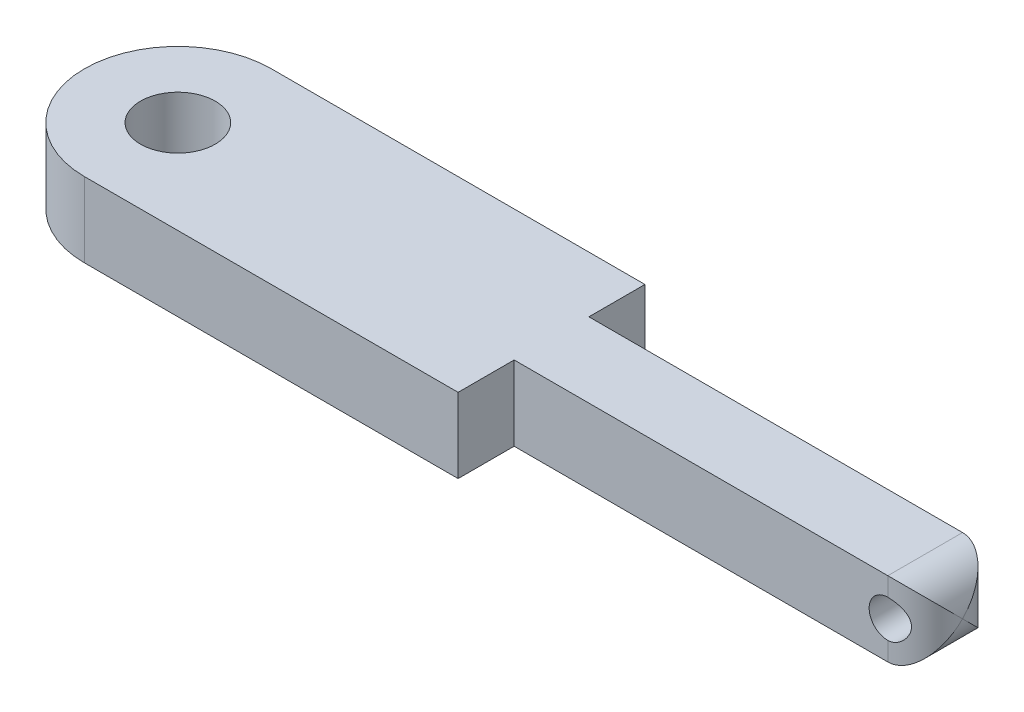
SolidWorks part; units mm, degrees
ref_plane "Front Plane" through (0, 0, 0) normal (0, 0, 1) x (1, 0, 0)
ref_plane "Top Plane" through (0, 0, 0) normal (0, 1, 0) x (1, 0, 0)
ref_plane "Right Plane" through (0, 0, 0) normal (1, 0, 0) x (0, 0, -1)
sketch "Sketch1" plane through (0, 0, 0) normal (0, 1, 0) x (1, 0, 0)
  line L0 (-10, 0) -> (0, 0) construction
  line L1 (-10, 2.5) -> (0, 2.5)
  line L2 (-10, -2.5) -> (0, -2.5)
  line L3 (0, 2.5) -> (0, -2.5)
  arc A0 (-10, 2.5) -> (-10, -2.5) centre (-10, 0) ccw
  circle A3 centre (-10, 0) radius 1
  point P3 (0, 0)
  dimension "D3" = 2
  dimension "D4" = 2.5
  dimension "D5" = 10
  dimension "D6" = 2.5
  dimension "D2" = 5
  dimension "D12" = 10
extrude "Boss-Extrude1" add sketch "Sketch1" along normal blind 2
sketch "Sketch2" plane through (0, 0, 0) normal (0, 0, 1) x (1, 0, 0)
  line L1 (0.0125, 0) -> (-0.0002, 0)
  line L5 (-10, 0) -> (0, 0) construction
  point P2 (0.0125, 1)
  dimension "D2" = 0
sketch "Sketch4" plane through (0, 0, 0) normal (1, 0, 0) x (0, 0, -1)
  line L1 (-1, 2) -> (1, 2)
  line L2 (-1, 2) -> (-1, 0)
  line L3 (-1, 0) -> (1, 0)
  line L4 (1, 2) -> (1, 0)
  line L5 (-1, 2) -> (1, 0) construction
  line L6 (-1, 0) -> (1, 2) construction
  point P0 (0, 1)
  dimension "D1" = 2
  dimension "D2" = 2
extrude "Boss-Extrude2" add sketch "Sketch4" along normal blind 11
ref_plane "Plane1" through (0, 0, 0) normal (0, 0, 1) x (1, 0, 0)
sketch "Sketch5" plane through (0, 2, 0) normal (0, 1, 0) x (1, 0, 0)
  line L2 (11, 1) -> (0, 1) construction
  line L3 (11, -1) -> (0, -1) construction
  line L4 (10, 1) -> (10, 1.5)
  line L5 (10, 1.5) -> (12, 1.5)
  line L6 (12, 1.5) -> (12, -1.5)
  line L7 (12, -1.5) -> (10, -1.5)
  line L8 (10, -1.5) -> (10, -1)
  line L9 (11, 1) -> (11, -1) construction
  arc A0 (10, 1) -> (10, -1) centre (10, 0) cw
  dimension "D1" = 1
  dimension "D2" = 3
  dimension "D3" = 0.5
  dimension "D4" = 2
extrude "Cut-Extrude1" cut sketch "Sketch5" against normal through all both
sketch "Sketch6" plane through (0, 0, -1) normal (0, 0, -1) x (-1, 0, 0)
  line L0 (-10, 0) -> (-10, 2) construction
  line L1 (-10, 2) -> (-10, 2.5)
  line L2 (-10, 2.5) -> (-12, 2.5)
  line L3 (-12, 2.5) -> (-12, -0.5)
  line L4 (-12, -0.5) -> (-10, -0.5)
  line L5 (-10, -0.5) -> (-10, 0)
  arc A0 (-10, 0) -> (-10, 2) centre (-10, 1) cw
  dimension "D1" = 0.5
  dimension "D2" = 3
  dimension "D4" = 2
  dimension "D5" = 2
extrude "Cut-Extrude2" cut sketch "Sketch6" against normal through all both
sketch "Sketch7" plane through (0, 0, -1) normal (0, 0, -1) x (-1, 0, 0)
  line L0 (-10, 0) -> (-10, 2) construction
  circle A0 centre (-10, 1) radius 0.5
extrude "Cut-Extrude3" cut sketch "Sketch7" against normal through all both
sketch "Sketch8" plane through (0, 0, 0) normal (0, 0, 1) x (1, 0, 0)
  line L0 (10, 1) -> (10, 0) construction
  line L1 (11, 1) -> (0, 1) construction
  line L2 (0, 2) -> (0, 0) construction
  arc A0 (10, 0) -> (11, 1) centre (10, 1) ccw construction
  arc A1 (11, 1) -> (10, 2) centre (10, 1) ccw construction
